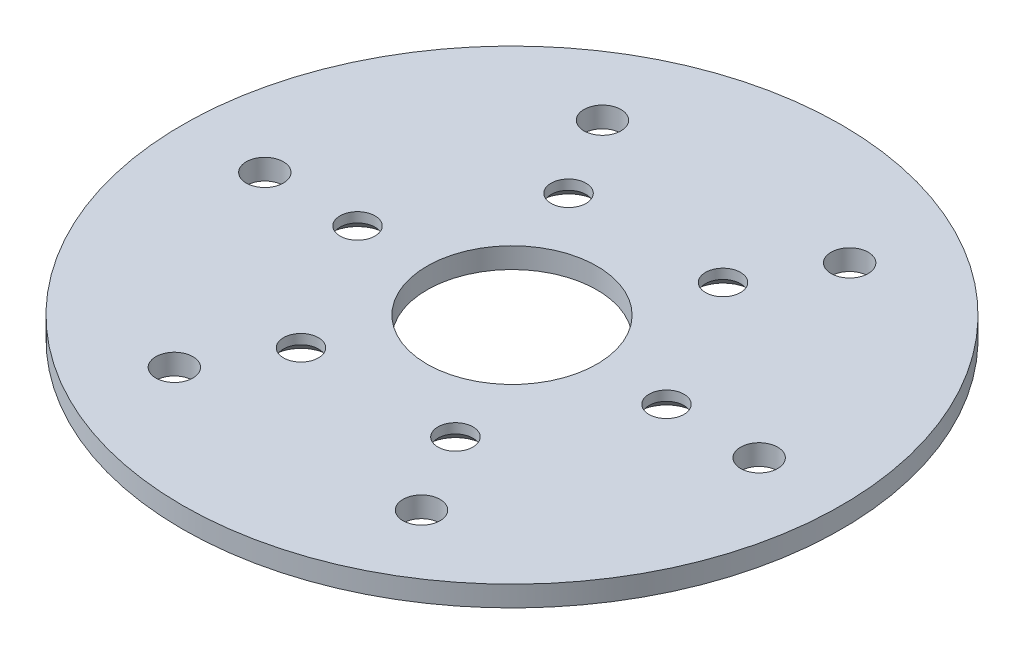
SolidWorks part; units mm, degrees
ref_plane "Front Plane" through (0, 0, 0) normal (0, 0, 1) x (1, 0, 0)
ref_plane "Top Plane" through (0, 0, 0) normal (0, 1, 0) x (1, 0, 0)
ref_plane "Right Plane" through (0, 0, 0) normal (1, 0, 0) x (0, 0, -1)
sketch "Sketch1" plane through (0, 0, 0) normal (0, 1, 0) x (1, 0, 0)
  circle A0 centre (0, 0) radius 8.25
  circle A1 centre (0, 0) radius 32
  dimension "D1" = 16.5
  dimension "D2" = 64
extrude "Boss-Extrude1" add sketch "Sketch1" along normal blind 2
sketch "Sketch2" plane through (0, 2, 0) normal (0, 1, 0) x (1, 0, 0)
  circle A0 centre (0, 21) radius 4
  circle A1 centre (0, 0) radius 21 construction
  circle A2 centre (18.1865, 10.5) radius 4
  circle A3 centre (18.1865, -10.5) radius 4
  circle A4 centre (0, -21) radius 4
  circle A5 centre (-18.1865, -10.5) radius 4
  circle A6 centre (-18.1865, 10.5) radius 4
  point P17 (0, 0)
  dimension "D1" = 8
  dimension "D2" = 42
  dimension "D3" = 6
extrude "Cut-Extrude1" [suppressed] cut sketch "Sketch2" against normal through all and the other way through all
hole_wizard "CSK for M3 Hex Socket Countersunk Head Screw1" positions "Sketch3" profile "Sketch4" countersink size "M3" standard "DIN" end condition up to next
sketch "Sketch3" plane through (0, 0, 0) normal (0, 1, 0) x (1, 0, 0)
  line L0 (0, 0) -> (18.891, 32.7202) construction
  circle A0 centre (0, 0) radius 15
  point P8 (7.5, 12.9904)
  point P14 (15, 0)
  point P15 (7.5, -12.9904)
  point P16 (-7.5, -12.9904)
  point P17 (-15, 0)
  point P18 (-7.5, 12.9904)
  dimension "D2" = 30
  dimension "D1" = 60
  dimension "D3" = 6
sketch "Sketch4" plane through (-7.5, 0, -12.9904) normal (1, 0, 0) x (0, 0, -1)
  line L0 (0, 0) -> (0, 2)
  line L1 (0, 2) -> (1.7, 2)
  line L2 (1.7, 2) -> (1.7, 1.05)
  line L3 (1.7, 1.05) -> (2.75, 0)
  line L5 (2.75, 0) -> (0, 0)
  line L6 (-1.7, 1.05) -> (-2.75, 0) construction
  line L11 (0, -6.35) -> (0, 107.95) construction
  dimension "Thru Hole Dia." = 3.4
  dimension "Thru Hole Depth" = 2
  dimension "Near C'Sink Dia." = 5.5
  dimension "Near C'Sink Angle" = 90
hole_wizard "M3 Clearance Hole1" positions "Sketch5" profile "Sketch7" hole size "M3" standard "DIN" end condition up to next
sketch "Sketch5" plane through (0, 0, 0) normal (0, -1, 0) x (-1, 0, 0)
  circle A0 centre (0, 0) radius 24
  point P6 (-24, 0)
  point P14 (-12, 20.7846)
  point P15 (12, 20.7846)
  point P16 (24, 0)
  point P17 (12, -20.7846)
  point P18 (-12, -20.7846)
  dimension "D1" = 48
sketch "Sketch7" plane through (12, 0, 20.7846) normal (1, 0, 0) x (0, 0, -1)
  line L0 (0, 0) -> (0, 2)
  line L1 (0, 2) -> (1.8, 2)
  line L2 (1.8, 2) -> (1.8, 0)
  line L5 (1.8, 0) -> (0, 0)
  line L11 (0, -6.35) -> (0, 107.95) construction
  dimension "Thru Hole Dia." = 3.6
  dimension "Thru Hole Depth" = 2
hole_wizard "Ø3.2 (3.2) Diameter Hole1" [suppressed] positions "Sketch8" profile "Sketch9" hole size "Ø3.2" standard "DIN"
sketch "Sketch8" plane through (0, 0, 0) normal (0, -1, 0) x (-1, 0, 0)
  circle A0 centre (0, 0) radius 15
  point P5 (0, 15)
  point P12 (12.9904, 7.5)
  point P13 (12.9904, -7.5)
  point P14 (0, -15)
  point P15 (-12.9904, -7.5)
  point P16 (-12.9904, 7.5)
  dimension "D1" = 30
  dimension "D2" = 6
sketch "Sketch9" plane through (12.9904, 0, -7.5) normal (1, 0, 0) x (0, 0, -1)
  line L0 (0, 0) -> (0, 2)
  line L1 (0, 2) -> (1.6, 2)
  line L2 (1.6, 2) -> (1.6, 0)
  line L5 (1.6, 0) -> (0, 0)
  line L11 (0, -6.35) -> (0, 107.95) construction
  dimension "Thru Hole Dia." = 3.2
  dimension "Thru Hole Depth" = 2
